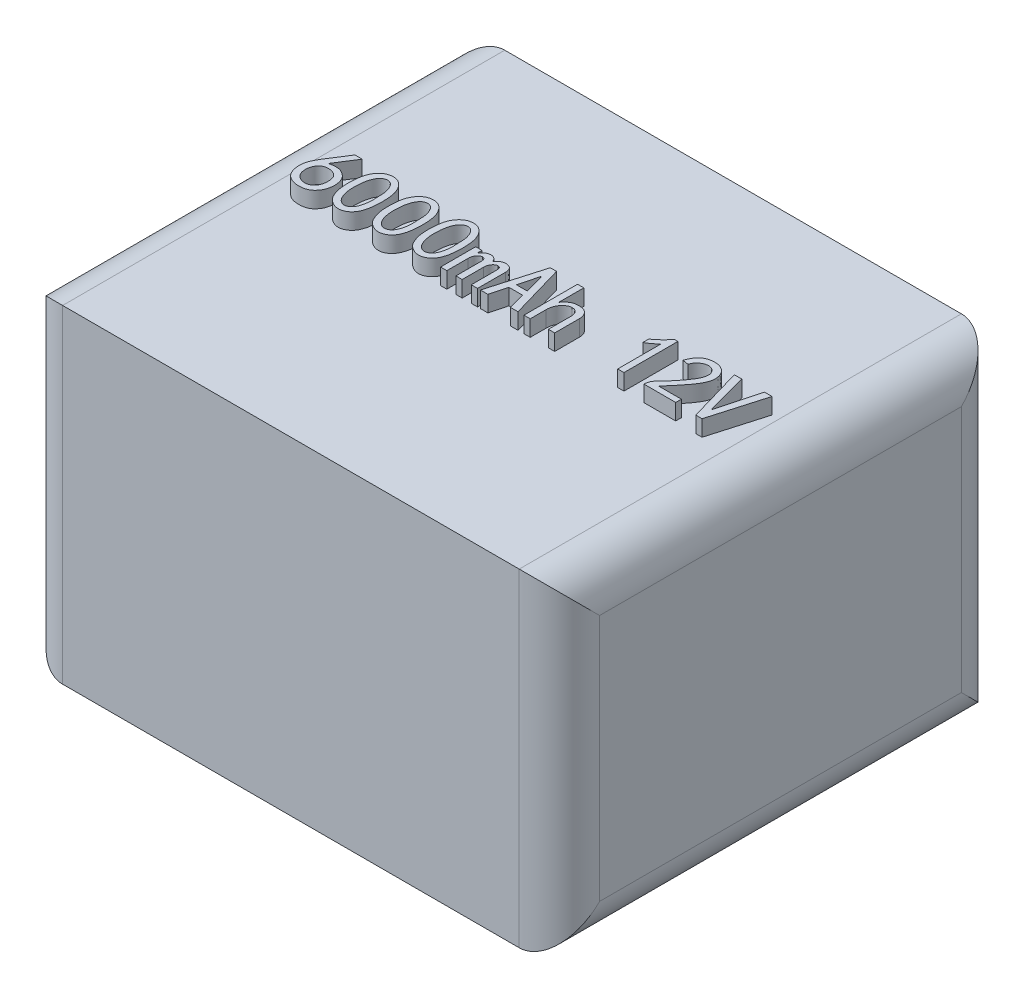
SolidWorks part; units mm, degrees
material "镍"
ref_plane "前视基准面" through (0, 0, 0) normal (0, 0, 1) x (1, 0, 0)
ref_plane "上视基准面" through (0, 0, 0) normal (0, 1, 0) x (1, 0, 0)
ref_plane "右视基准面" through (0, 0, 0) normal (1, 0, 0) x (0, 0, -1)
sketch "草图1" plane through (0, 0, 0) normal (0, 1, 0) x (1, 0, 0)
  line L1 (0, 0) -> (66.8, 0)
  line L2 (0, 0) -> (0, 55)
  line L3 (0, 55) -> (66.8, 55)
  line L4 (66.8, 0) -> (66.8, 55)
  dimension "D1" = 66.8
  dimension "D2" = 55
extrude "凸台-拉伸1" add sketch "草图1" along normal blind 40.8
fillet "圆角1" radius 5 8 edges at (0, 20.4, -55) (0, 40.8, -27.5) (0, 20.4, 0) (0, 0, -27.5) (66.8, 20.4, 0) (66.8, 40.8, -27.5) (66.8, 20.4, -55) (66.8, 0, -27.5)
sketch "草图3" plane through (0, 40.8, 0) normal (0, 1, 0) x (1, 0, 0)
  text T0 "6000mAh 12V" font "黑体" height in points 22
extrude "凸台-拉伸2" add sketch "草图3" along normal blind 2
